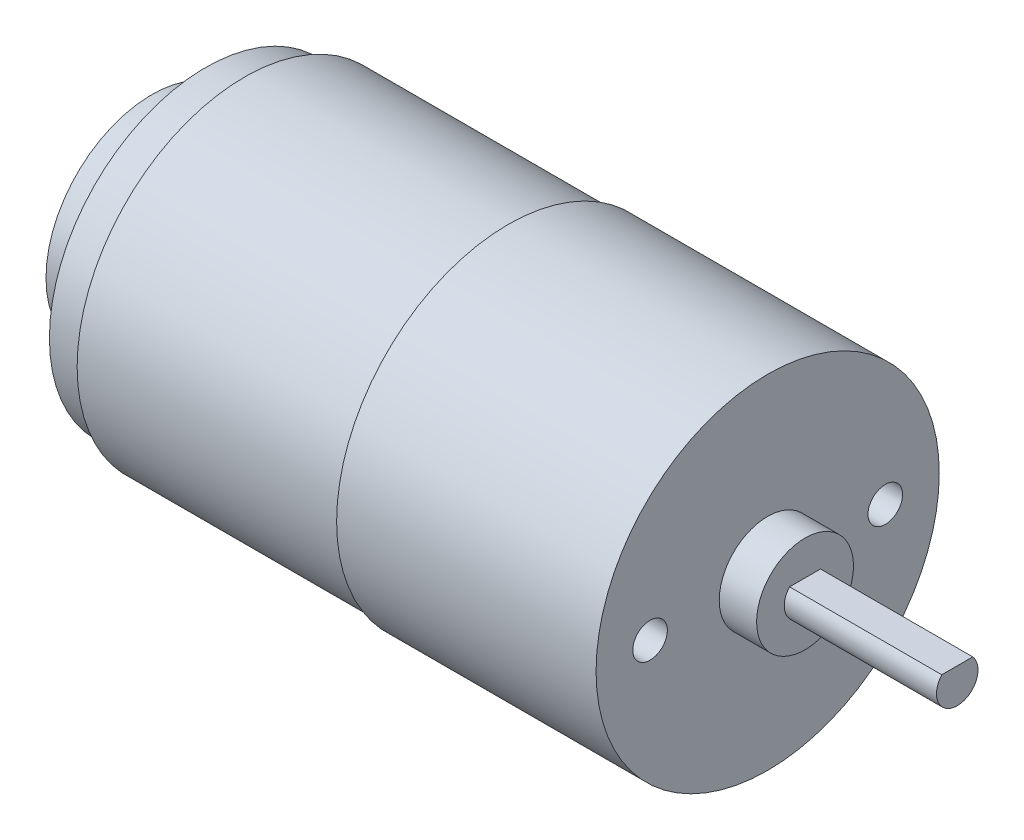
SolidWorks part; units mm, degrees
ref_plane "前视基准面" through (0, 0, 0) normal (0, 0, 1) x (1, 0, 0)
ref_plane "上视基准面" through (0, 0, 0) normal (0, 1, 0) x (1, 0, 0)
ref_plane "右视基准面" through (0, 0, 0) normal (1, 0, 0) x (0, 0, -1)
sketch "草图1" plane through (0, 0, 0) normal (0, 0, 1) x (1, 0, 0)
  line L0 (-38.0292, 0) -> (36.3074, 0) construction
  line L1 (-29.1738, 0) -> (-29.1738, 7.6501)
  line L2 (-29.1738, 7.6501) -> (-25.2872, 7.6501)
  line L3 (-25.2872, 7.6501) -> (-25.2872, 11.2907)
  line L4 (-25.2872, 11.2907) -> (-22.4738, 11.2907)
  line L5 (-22.4738, 11.2907) -> (-22.4738, 12.1)
  line L6 (-22.4738, 12.1) -> (-3.4238, 12.1)
  line L7 (-3.4238, 12.1) -> (-3.4238, 12.4)
  line L8 (-3.4238, 12.4) -> (15.3262, 12.4)
  line L9 (15.3262, 12.4) -> (15.3262, 3.5)
  line L10 (15.3262, 3.5) -> (18.0262, 3.5)
  line L11 (18.0262, 3.5) -> (18.0262, 1.5)
  line L12 (18.0262, 1.5) -> (29.0262, 1.5)
  line L13 (29.0262, 1.5) -> (29.0262, 0)
  line L14 (29.0262, 0) -> (-29.1738, 0)
  dimension "D1" = 58.2
  dimension "D2" = 19.05
  dimension "D3" = 18.75
  dimension "D4" = 2.7
  dimension "D5" = 11
  dimension "D6" = 12.1
  dimension "D7" = 12.4
  dimension "D8" = 3.8866
  dimension "D9" = 1.5
  dimension "D10" = 3.5
revolve "旋转1" add sketch "草图1" angle 360 about L0
sketch "草图2" plane through (29.0262, 0, 0) normal (1, 0, 0) x (0, 0, -1)
  line L0 (-1.118, 1) -> (1.118, 1)
  circle A0 centre (0, 0) radius 1.5
  circle M2 centre (0, 0) radius 1.5
  dimension "D2" = 3
  dimension "D1" = 1
extrude "切除-拉伸3" cut sketch "草图2" against normal blind 11 contours L0 M2
sketch "草图3" plane through (15.3262, 0, 0) normal (1, 0, 0) x (0, 0, -1)
  line L0 (-14.7475, 0) -> (13.9754, 0) construction
  line L1 (0, 13.2902) -> (0, -13.3095) construction
  circle A0 centre (-8.5, 0) radius 1.25
  circle A1 centre (8.5, 0) radius 1.25
  dimension "D2" = 2.5
  dimension "D1" = 17
extrude "切除-拉伸4" cut sketch "草图3" against normal blind 13 contours A1 | A0
